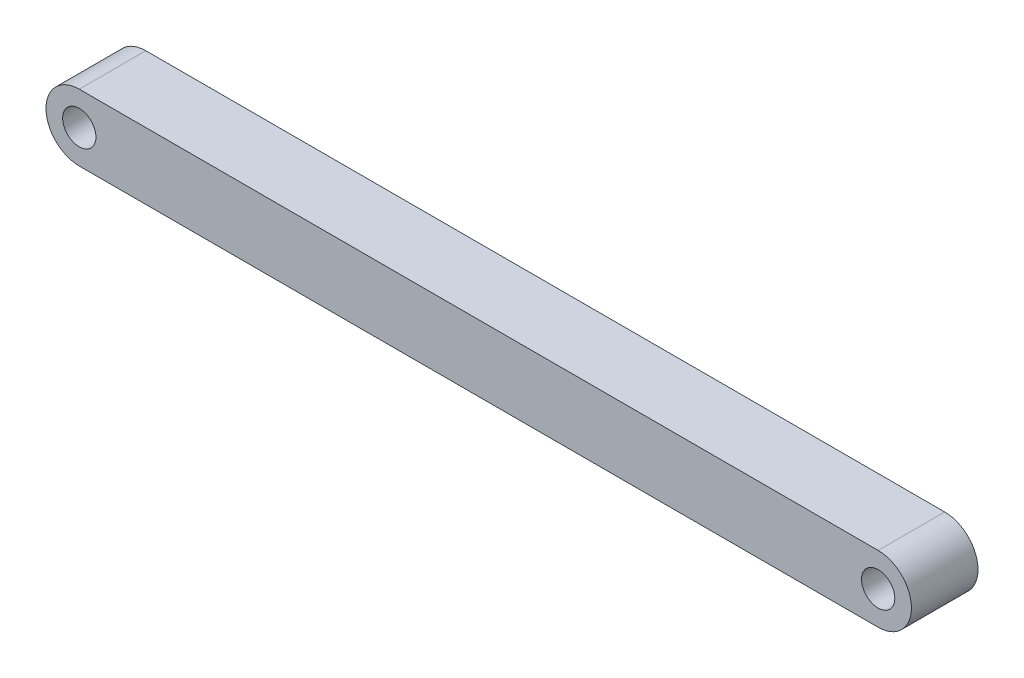
SolidWorks part; units mm, degrees
ref_plane "前视基准面" through (0, 0, 0) normal (0, 0, 1) x (1, 0, 0)
ref_plane "上视基准面" through (0, 0, 0) normal (0, 1, 0) x (1, 0, 0)
ref_plane "右视基准面" through (0, 0, 0) normal (1, 0, 0) x (0, 0, -1)
ref_plane "基准面4" through (0, 0, 21) normal (0, 0, 1) x (1, 0, 0)
sketch "草图2" plane through (0, 0, 21) normal (0, 0, 1) x (1, 0, 0)
  line L0 (100, 35) -> (108.2772, 65.4293) construction
  line L1 (100, 35) -> (184.4213, 35) construction
  line L2 (108.2772, 65.4293) -> (228.2772, 65.4293) construction
  line L3 (108.2772, 70.4293) -> (228.2772, 70.4293)
  line L4 (108.2772, 60.4293) -> (228.2772, 60.4293)
  arc A0 (108.2772, 70.4293) -> (108.2772, 60.4293) centre (108.2772, 65.4293) ccw
  arc A1 (228.2772, 60.4293) -> (228.2772, 70.4293) centre (228.2772, 65.4293) ccw
  circle A2 centre (108.2772, 65.4293) radius 2.5
  circle A3 centre (228.2772, 65.4293) radius 2.5
  point P5 (168.2772, 65.4293)
  dimension "D1" = 31.535
  dimension "D2" = 74.783
  dimension "D3" = 120
  dimension "D4" = 10
extrude "凸台-拉伸1" add sketch "草图2" along normal blind 10
